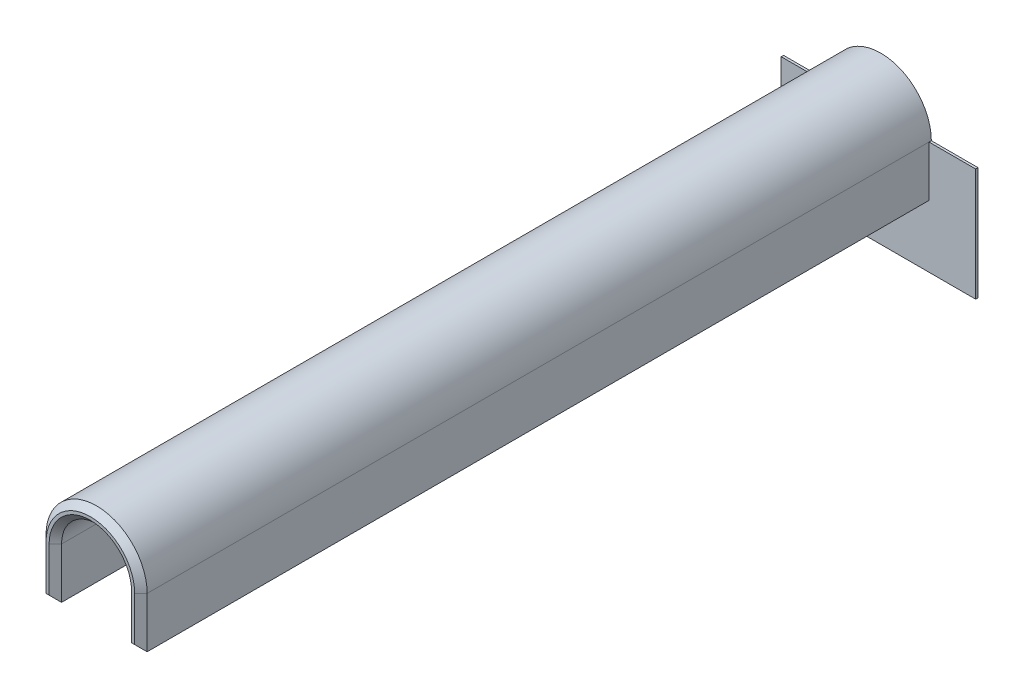
SolidWorks part; units mm, degrees
ref_plane "Front Plane" through (0, 0, 0) normal (0, 0, 1) x (1, 0, 0)
ref_plane "Top Plane" through (0, 0, 0) normal (0, 1, 0) x (1, 0, 0)
ref_plane "Right Plane" through (0, 0, 0) normal (1, 0, 0) x (0, 0, -1)
sketch "Sketch1" plane through (0, 0, 0) normal (0, 0, 1) x (1, 0, 0)
  line L0 (-4.5, 0) -> (-4.5, -6.5)
  line L1 (-4.5, -6.5) -> (-6.5, -6.5)
  line L2 (-6.5, -6.5) -> (-6.5, 0)
  line L3 (4.5, 0) -> (4.5, -6.5)
  line L4 (4.5, -6.5) -> (6.5, -6.5)
  line L5 (6.5, -6.5) -> (6.5, 0)
  arc A0 (-4.5, 0) -> (4.5, 0) centre (0, 0) cw
  arc A1 (-6.5, 0) -> (6.5, 0) centre (0, 0) cw
  circle A2 centre (0, 0) radius 4.5 construction
  point P11 (0, -4.5)
  dimension "D3" = 9
  dimension "D1" = 2
  dimension "D2" = 2
extrude "Boss-Extrude1" add sketch "Sketch1" along normal blind 101.6
sketch "Sketch2" plane through (0, 0, 0) normal (0, 0, -1) x (-1, 0, 0)
  line L0 (4.5, 0) -> (4.5, -6.5) construction
  line L1 (-4.5, 0) -> (-4.5, -6.5) construction
  line L2 (4.5, 0) -> (4.5, -6.5)
  line L3 (-4.5, 0) -> (-4.5, -6.5)
  line L4 (-4.5, 0) -> (-12.5, 0)
  line L5 (-12.5, 0) -> (-12.5, -14.5)
  line L6 (-12.5, -14.5) -> (12.5, -14.5)
  line L7 (12.5, -14.5) -> (12.5, 0)
  line L8 (12.5, 0) -> (4.5, 0)
  line L9 (4.5, -6.5) -> (-4.5, -6.5)
  line L10 (0.7796, -6.5) -> (0.7796, -14.5) construction
  point P11 (2.4708, -14.5)
  point P12 (0.7796, -14.5)
  dimension "D1" = 8
extrude "Boss-Extrude2" add sketch "Sketch2" against normal blind 0.3
chamfer "Chamfer1" distance 0.8 angle 45 8 edges at (-4.5, -3.25, 101.6) (-5.5, -6.5, 101.6) (-6.5, -3.25, 101.6) (0, 6.5, 101.6) (6.5, -3.25, 101.6) (5.5, -6.5, 101.6) (4.5, -3.25, 101.6) (0, 4.5, 101.6)
